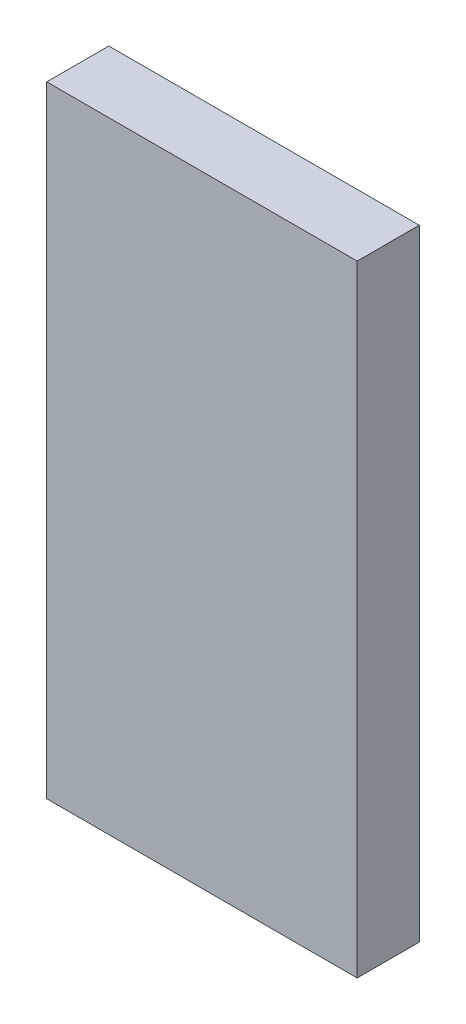
SolidWorks part; units mm, degrees
material "AISI 1020"
ref_plane "Alzado" through (0, 0, 0) normal (0, 0, 1) x (1, 0, 0)
ref_plane "Planta" through (0, 0, 0) normal (0, 1, 0) x (1, 0, 0)
ref_plane "Vista lateral" through (0, 0, 0) normal (1, 0, 0) x (0, 0, -1)
sketch "Croquis1" plane through (0, 0, 0) normal (0, 0, 1) x (1, 0, 0)
  line L1 (-30, -60) -> (30, -60)
  line L2 (-30, -60) -> (-30, 60)
  line L3 (-30, 60) -> (30, 60)
  line L4 (30, -60) -> (30, 60)
  line L5 (-30, -60) -> (30, 60) construction
  line L6 (-30, 60) -> (30, -60) construction
  point P0 (0, 0)
  dimension "D1" = 60
  dimension "D2" = 120
extrude "Saliente-Extruir1" add sketch "Croquis1" along normal blind 12
